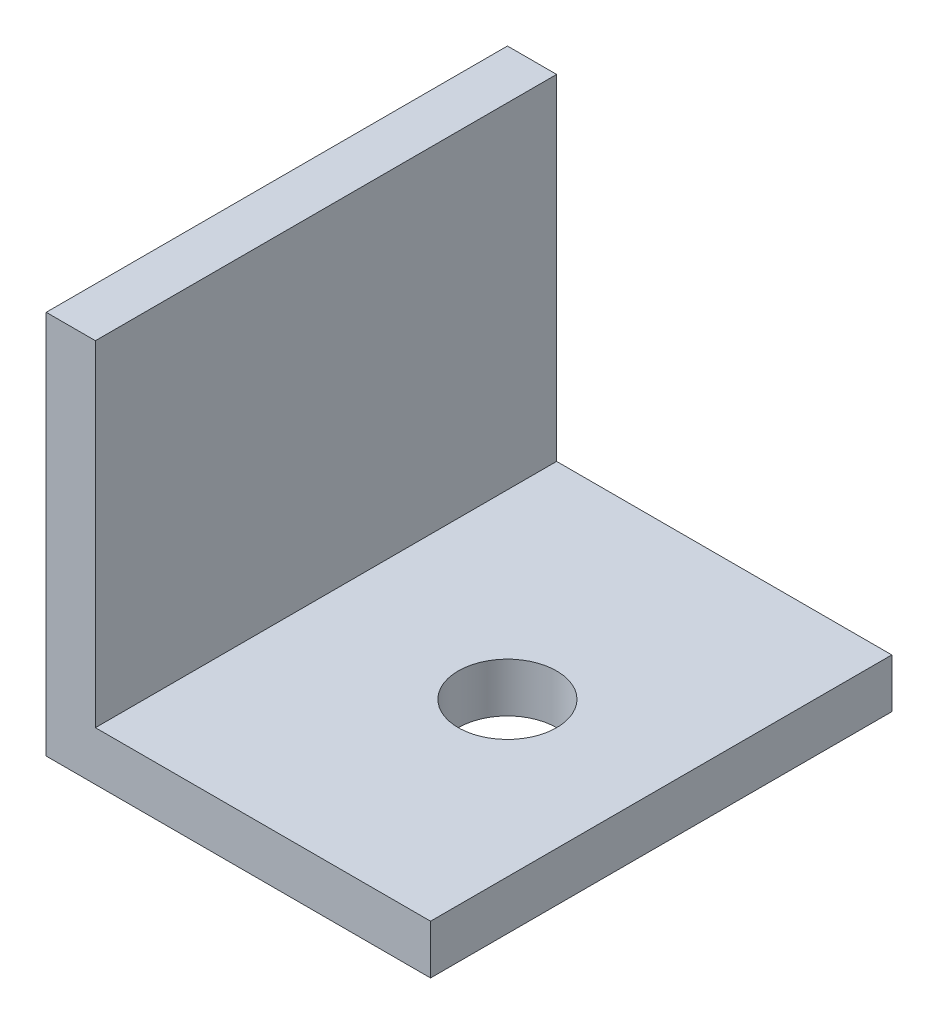
SolidWorks part; units mm, degrees
ref_plane "Front Plane" through (0, 0, 0) normal (0, 0, 1) x (1, 0, 0)
ref_plane "Top Plane" through (0, 0, 0) normal (0, 1, 0) x (1, 0, 0)
ref_plane "Right Plane" through (0, 0, 0) normal (1, 0, 0) x (0, 0, -1)
sketch "Sketch1" plane through (0, 0, 0) normal (0, 0, 1) x (1, 0, 0)
  line L0 (0, 0) -> (0, 12.5)
  line L1 (0, 12.5) -> (1.6, 12.5)
  line L2 (1.6, 12.5) -> (1.6, 1.6)
  line L3 (1.6, 1.6) -> (12.5, 1.6)
  line L4 (12.5, 1.6) -> (12.5, 0)
  line L5 (12.5, 0) -> (0, 0)
  dimension "D1" = 12.5
  dimension "D2" = 1.6
extrude "Boss-Extrude1" add sketch "Sketch1" along normal blind 15
sketch "Sketch2" plane through (0, 1.6, 0) normal (0, 1, 0) x (1, 0, 0)
  line L0 (7.5, 0) -> (7.5, -15) construction
  line L1 (12.5, 0) -> (1.6, 0) construction
  line L2 (12.5, -15) -> (1.6, -15) construction
  line L3 (12.5, -15) -> (12.5, 0) construction
  circle A0 centre (7.5, -7.5) radius 1.6
  dimension "D2" = 3.2
  dimension "D1" = 5
extrude "Cut-Extrude1" cut sketch "Sketch2" against normal through all
